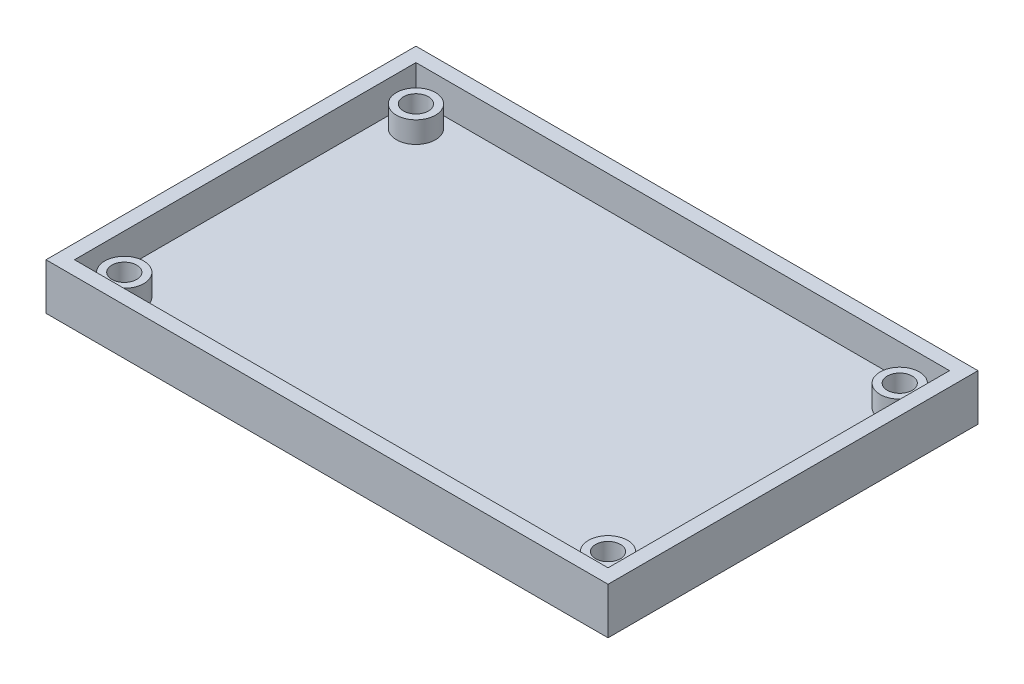
SolidWorks part; units mm, degrees
ref_plane "Front Plane" through (0, 0, 0) normal (0, 0, 1) x (1, 0, 0)
ref_plane "Top Plane" through (0, 0, 0) normal (0, 1, 0) x (1, 0, 0)
ref_plane "Right Plane" through (0, 0, 0) normal (1, 0, 0) x (0, 0, -1)
sketch "Sketch1" plane through (0, 0, 0) normal (0, 1, 0) x (1, 0, 0)
  line L1 (-37.5, 24) -> (37.5, 24)
  line L2 (-37.5, 24) -> (-37.5, -24)
  line L3 (-37.5, -24) -> (37.5, -24)
  line L4 (37.5, 24) -> (37.5, -24)
  line L5 (-37.5, 24) -> (37.5, -24) construction
  line L6 (-37.5, -24) -> (37.5, 24) construction
  line L7 (-39.5, 26) -> (39.5, 26)
  line L8 (-39.5, 26) -> (-39.5, -26)
  line L9 (-39.5, -26) -> (39.5, -26)
  line L10 (39.5, 26) -> (39.5, -26)
  line L11 (-39.5, 26) -> (39.5, -26) construction
  line L12 (-39.5, -26) -> (39.5, 26) construction
  point P0 (0, 0)
  point P6 (0, 0)
  dimension "D1" = 75
  dimension "D2" = 48
  dimension "D3" = 2
  dimension "D4" = 2
extrude "Boss-Extrude1" add sketch "Sketch1" along normal blind 4.524
sketch "Sketch2" plane through (0, 0, 0) normal (0, -1, 0) x (1, 0, 0)
  line L1 (39.5, 26) -> (-39.5, 26)
  line L2 (39.5, 26) -> (39.5, -26)
  line L3 (39.5, -26) -> (-39.5, -26)
  line L4 (-39.5, 26) -> (-39.5, -26)
  line L5 (39.5, 26) -> (-39.5, -26) construction
  line L6 (39.5, -26) -> (-39.5, 26) construction
  point P0 (0, 0)
extrude "Boss-Extrude2" add sketch "Sketch2" along normal blind 2
sketch "Sketch3" plane through (0, 0, 0) normal (0, 1, 0) x (1, 0, 0)
  line L0 (37.5, 24) -> (-37.5, 24) construction
  line L1 (-37.5, 24) -> (-37.5, -24) construction
  line L2 (-37.5, -24) -> (37.5, -24) construction
  line L3 (37.5, -24) -> (37.5, 24) construction
  circle A0 centre (-34, 20.5) radius 1.9
  circle A1 centre (34, 20.5) radius 1.9
  circle A2 centre (34, -20.5) radius 1.9
  circle A3 centre (-34, -20.5) radius 1.9
  dimension "D1" = 3.8
  dimension "D2" = 3.8
  dimension "D3" = 3.8
  dimension "D4" = 3.8
  dimension "D5" = 3.5
  dimension "D6" = 3.5
  dimension "D7" = 3.5
  dimension "D8" = 3.5
  dimension "D9" = 3.5
  dimension "D10" = 3.5
  dimension "D11" = 3.5
  dimension "D12" = 3.5
extrude "Cut-Extrude1" cut sketch "Sketch3" against normal blind 2
sketch "Sketch4" plane through (0, 0, 0) normal (0, 1, 0) x (1, 0, 0)
  circle A0 centre (-34, -20.5) radius 2.75
  circle A1 centre (-34, -20.5) radius 1.75
  circle A2 centre (34, -20.5) radius 1.75
  circle A3 centre (34, -20.5) radius 2.75
  circle A4 centre (34, 20.5) radius 1.75
  circle A5 centre (34, 20.5) radius 2.75
  circle A6 centre (-34, 20.5) radius 1.75
  circle A7 centre (-34, 20.5) radius 2.75
  dimension "D1" = 1
  dimension "D2" = 1
  dimension "D3" = 1
  dimension "D4" = 1
extrude "Boss-Extrude3" add sketch "Sketch4" along normal blind 3
